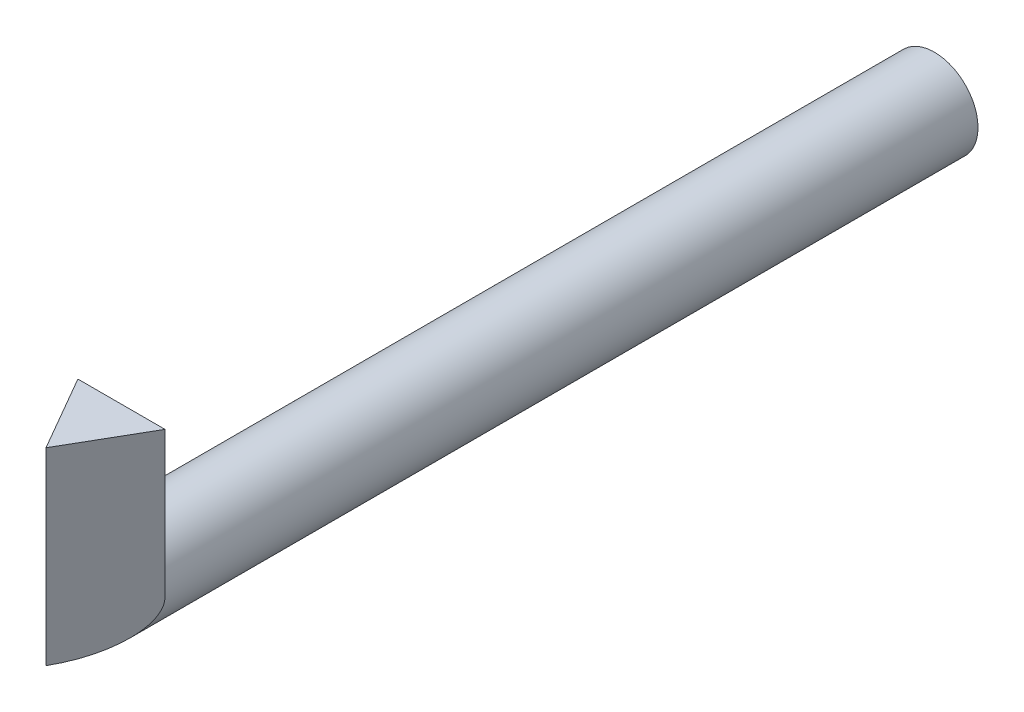
SolidWorks part; units mm, degrees
ref_plane "前视基准面" through (0, 0, 0) normal (0, 0, 1) x (1, 0, 0)
ref_plane "上视基准面" through (0, 0, 0) normal (0, 1, 0) x (1, 0, 0)
ref_plane "右视基准面" through (0, 0, 0) normal (1, 0, 0) x (0, 0, -1)
other "Configuration Table"
sketch "草图5" plane through (0, 0, 0) normal (0, 0, 1) x (1, 0, 0)
  circle A0 centre (0, 0) radius 1.5
  point P2 (0, 0)
  dimension "D1" = 3
extrude "凸台-拉伸4" add sketch "草图5" along normal blind 31
sketch "草图6" plane through (0, 0, 31) normal (0, 0, 1) x (1, 0, 0)
  line L1 (-1.5, 1.5) -> (1.5, 1.5)
  line L2 (-1.5, 1.5) -> (-1.5, 0)
  line L3 (-1.5, 0) -> (1.5, 0)
  line L4 (1.5, 1.5) -> (1.5, 0)
  line L5 (-1.5, 1.5) -> (1.5, 0) construction
  line L6 (-1.5, 0) -> (1.5, 1.5) construction
  point P0 (0, 0.75)
  point P5 (0, 0)
  dimension "D1" = 3
  dimension "D2" = 1.5
extrude "切除-拉伸2" cut sketch "草图6" against normal blind 3
sketch "草图7" plane through (0, 0, 0) normal (0, 1, 0) x (1, 0, 0)
  line L2 (-1.5, -28) -> (0, -30.5981)
  line L3 (0, -30.5981) -> (1.5, -28)
  line L4 (-1.5, -28) -> (-1.5, -31)
  line L5 (-1.5, -31) -> (1.5, -31)
  line L6 (1.5, -31) -> (1.5, -28)
  line L8 (1.5, -28) -> (0, -28) [skipped]
  dimension "D1" = 3
extrude "切除-拉伸3" cut sketch "草图7" against normal blind 1.5
sketch "草图8" plane through (0, 0, 0) normal (0, 1, 0) x (1, 0, 0)
  line L0 (-1.5, -28) -> (1.5, -28) construction
  line L1 (0, -30.5981) -> (1.5, -28)
  line L2 (1.5, -28) -> (-1.5, -28)
  line L3 (-1.5, -28) -> (0, -30.5981)
  circle A0 centre (0, -28.866) radius 0.866 construction
  point P7 (0, 0)
  dimension "D1" = 3
extrude "凸台-拉伸5" add sketch "草图8" along normal blind 5
